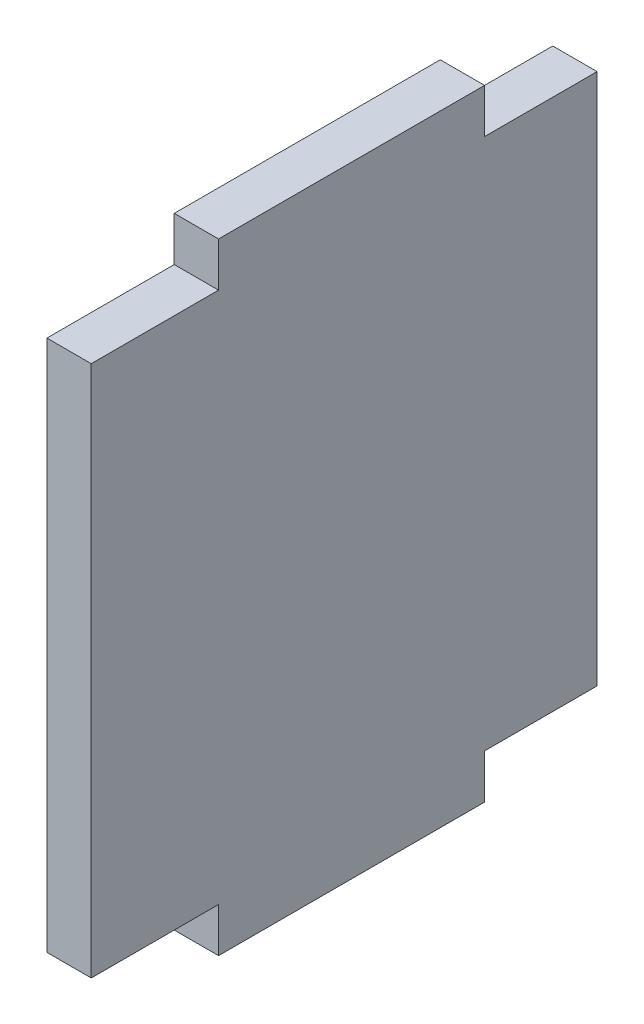
SolidWorks part; units mm, degrees
material "Maple"
ref_plane "Front Plane" through (0, 0, 0) normal (0, 0, 1) x (1, 0, 0)
ref_plane "Top Plane" through (0, 0, 0) normal (0, 1, 0) x (1, 0, 0)
ref_plane "Right Plane" through (0, 0, 0) normal (1, 0, 0) x (0, 0, -1)
sketch "Sketch1" plane through (0, 0, 0) normal (1, 0, 0) x (0, 0, -1)
  line L0 (-7.6594, 0) -> (6.6904, 0) construction
  line L1 (-13.195, -15) -> (13.195, -15) construction
  line L3 (-13.195, 15) -> (13.195, 15) construction
  line L4 (13.195, -15) -> (13.195, 15)
  line L5 (-13.195, -15) -> (13.195, 15) construction
  line L6 (-13.195, 15) -> (13.195, -15) construction
  line L7 (-13.195, 17.5) -> (13.195, 17.5) construction
  line L8 (-13.195, -17.5) -> (13.195, -17.5) construction
  line L10 (-8.1495, 15) -> (-8.1495, 17.5)
  line L11 (-8.1495, 17.5) -> (6.8505, 17.5)
  line L12 (6.8505, 17.5) -> (6.8505, 15)
  line L13 (6.8505, 15) -> (13.195, 15)
  line L14 (6.8505, -15) -> (13.195, -15)
  line L15 (6.8505, -17.5) -> (6.8505, -15)
  line L16 (-8.1495, -17.5) -> (6.8505, -17.5)
  line L18 (-8.1495, -15) -> (-8.1495, -17.5)
  line L19 (-15.3295, 15) -> (-15.3295, -15)
  line L20 (-8.1495, 15) -> (-15.3295, 15)
  line L21 (-15.3295, -15) -> (-8.1495, -15)
  point P0 (0, 0)
  dimension "D1" = 26.39
  dimension "D2" = 30
  dimension "D5" = 15
  dimension "D6" = 6.3445
  dimension "D7" = 7.18
  dimension "D3" = 2.5
  dimension "D4" = 2.5
extrude "Boss-Extrude1" add sketch "Sketch1" along normal mid plane 2.5
